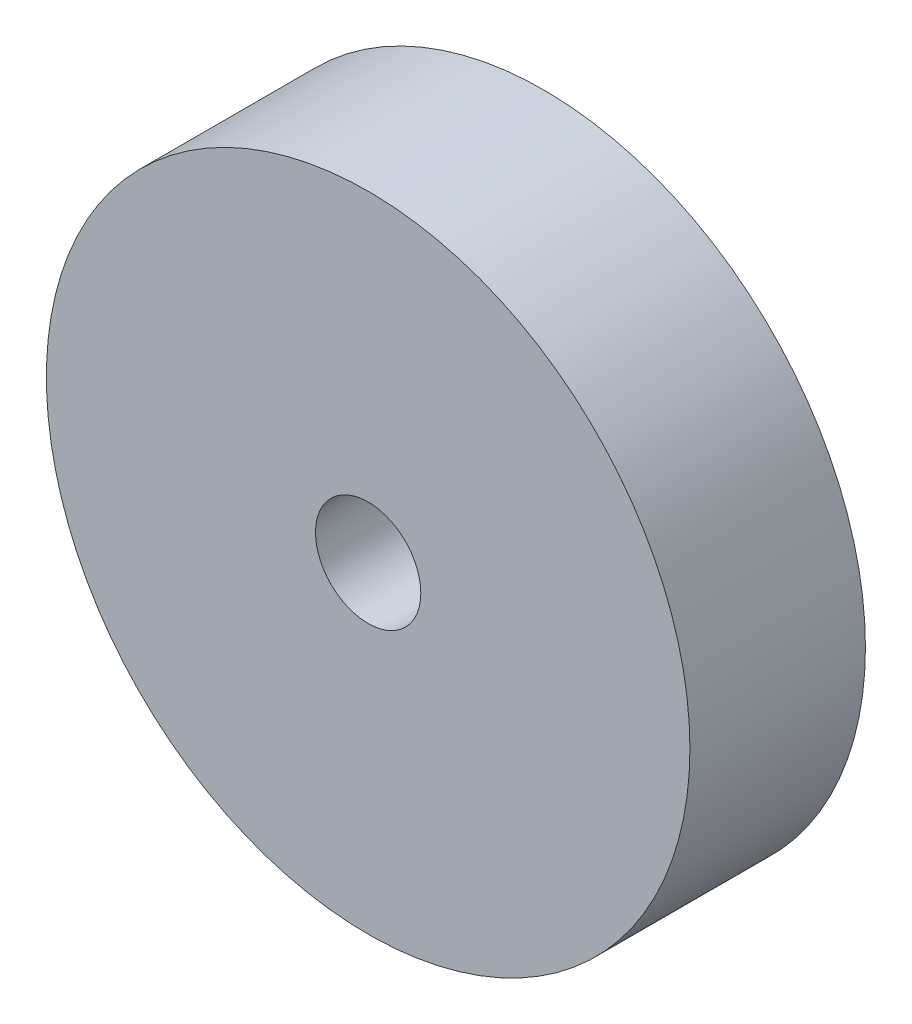
SolidWorks part; units mm, degrees
ref_plane "Front Plane" through (0, 0, 0) normal (0, 0, 1) x (1, 0, 0)
ref_plane "Top Plane" through (0, 0, 0) normal (0, 1, 0) x (1, 0, 0)
ref_plane "Right Plane" through (0, 0, 0) normal (1, 0, 0) x (0, 0, -1)
sketch "Sketch1" plane through (0, 0, 0) normal (0, 0, 1) x (1, 0, 0)
  circle A0 centre (0, 0) radius 5.5
  circle A1 centre (0, 0) radius 0.9
extrude "Boss-Extrude1" add sketch "Sketch1" along normal blind 3 contours A0 A1
